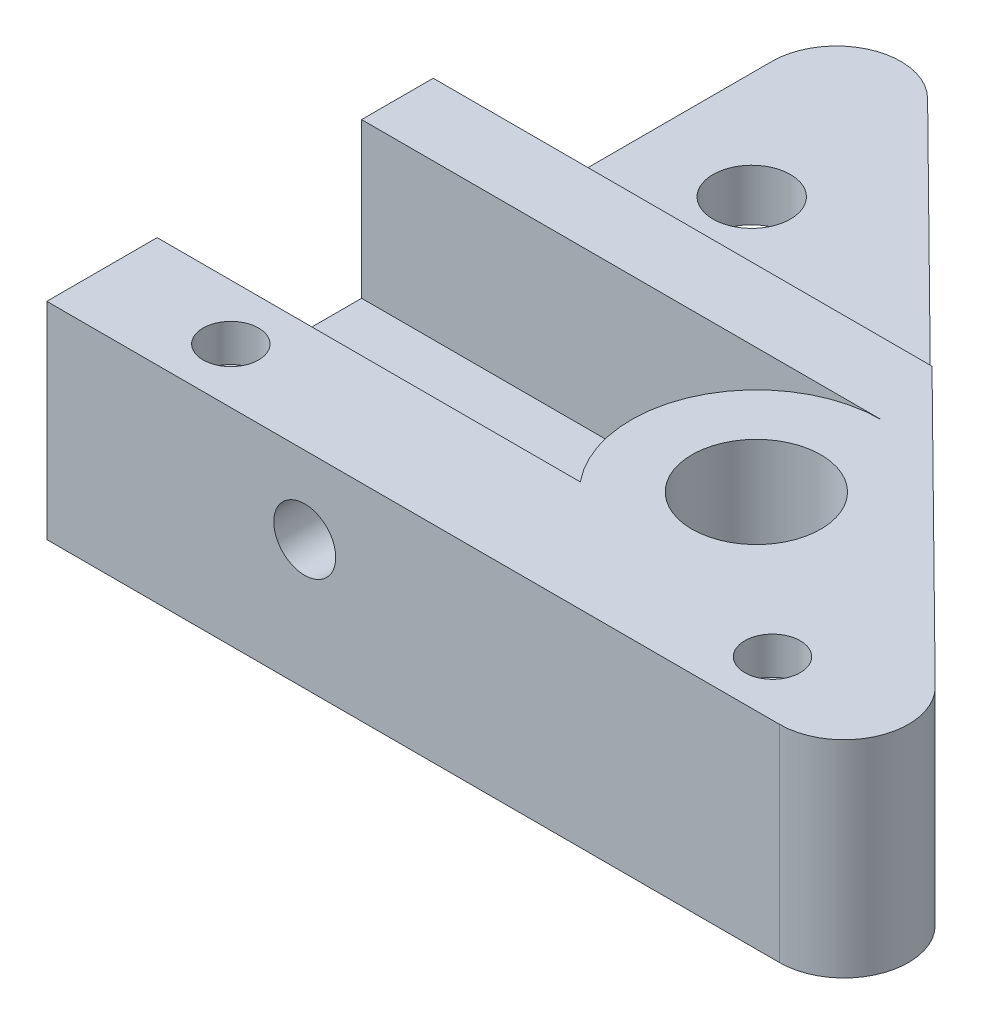
SolidWorks part; units mm, degrees
ref_plane "Front Plane" through (0, 0, 0) normal (0, 0, 1) x (1, 0, 0)
ref_plane "Top Plane" through (0, 0, 0) normal (0, 1, 0) x (1, 0, 0)
ref_plane "Right Plane" through (0, 0, 0) normal (1, 0, 0) x (0, 0, -1)
sketch "Sketch1" plane through (0, 0, 0) normal (0, 1, 0) x (1, 0, 0)
  line L0 (-5.7903, 58.3474) -> (-5.7903, -9.8521)
  line L1 (-5.7903, -9.8521) -> (63.1931, -9.8521)
  line L2 (-5.7903, 58.3474) -> (63.1931, -9.8521)
  circle A0 centre (2.5214, 36.4964) radius 3
  circle A1 centre (34.52, 4.8564) radius 5
  dimension "D2" = 6
  dimension "D3" = 10
  dimension "D1" = 45
  dimension "D4" = 31.64
  dimension "D5" = 31.9986
extrude "Boss-Extrude1" add sketch "Sketch1" along normal blind 4
fillet "Fillet1" radius 5 2 edges at (-5.7903, 2, -58.3474) (63.1931, 2, 9.8521)
sketch "Sketch2" plane through (0, 4, 0) normal (0, 1, 0) x (1, 0, 0)
  line L0 (54.5391, -1.2965) -> (-5.7903, -1.2965)
  line L1 (54.5391, -1.2965) -> (41.3389, 11.7537)
  line L2 (34.52, 14.5554) -> (-5.7903, 14.5554)
  line L3 (54.5391, -1.2965) -> (2.7249, 49.9289)
  line L4 (-5.7903, 46.3732) -> (-5.7903, -9.8521)
  line L5 (-5.7903, -9.8521) -> (51.0238, -9.8521)
  line L6 (54.5391, -1.2965) -> (2.7249, 49.9289)
  line L7 (-5.7903, 46.3732) -> (-5.7903, -9.8521)
  line L8 (-5.7903, -9.8521) -> (51.0238, -9.8521)
  line L9 (-5.7903, 20.1092) -> (32.8874, 20.1092)
  line L10 (54.5391, -1.2965) -> (2.7249, 49.9289)
  circle A0 centre (34.52, 4.8564) radius 9.699
  arc A2 (2.7249, 49.9289) -> (-5.7903, 46.3732) centre (-0.7903, 46.3732) ccw
  arc A3 (51.0238, -9.8521) -> (54.5391, -1.2965) centre (51.0238, -4.8521) ccw
  arc A4 (2.7249, 49.9289) -> (-5.7903, 46.3732) centre (-0.7903, 46.3732) ccw
  arc A5 (51.0238, -9.8521) -> (54.5391, -1.2965) centre (51.0238, -4.8521) ccw
  line M6 (54.5391, -1.2965) -> (2.7249, 49.9289)
  line M8 (-5.7903, 46.3732) -> (-5.7903, -9.8521)
  line M9 (-5.7903, -9.8521) -> (51.0238, -9.8521)
  arc M10 (51.0238, -9.8521) -> (54.5391, -1.2965) centre (51.0238, -4.8521) ccw
  circle M12 centre (34.52, 4.8564) radius 5
  dimension "D1" = 0
extrude "Boss-Extrude2" add sketch "Sketch2" along normal blind 12 contours A0 L0 M6 | A0 L0 M8 M9 M10 | L0 A0 | A0 L9 L7 L2 M6 | L0 A0 M12
sketch "Sketch4" plane through (0, 0, 1.2965) normal (0, 0, -1) x (-1, 0, 0)
  line L0 (-27.0224, 4) -> (5.7903, 4) construction
  line L2 (5.7903, 16) -> (5.7903, 4) construction
  circle A0 centre (-14.2097, 10) radius 2.4019
  point P8 (5.7903, 10)
  dimension "D1" = 6
  dimension "D2" = 20
extrude "Cut-Extrude2" cut sketch "Sketch4" against normal blind 30
sketch "Sketch6" plane through (0, 16, 0) normal (0, 1, 0) x (1, 0, 0)
  line L0 (-5.7903, -9.8521) -> (51.0238, -9.8521) construction
  line L2 (-5.7903, -1.2965) -> (-5.7903, -9.8521) construction
  circle A0 centre (46.2097, -5.5821) radius 2.15
  circle A1 centre (4.2097, -5.5821) radius 2.15
  dimension "D1" = 4.3
  dimension "D2" = 4.3
  dimension "D4" = 4.27
  dimension "D3" = 4.27
  dimension "D5" = 10
  dimension "D6" = 52
extrude "Cut-Extrude3" cut sketch "Sketch6" against normal blind 2.9
